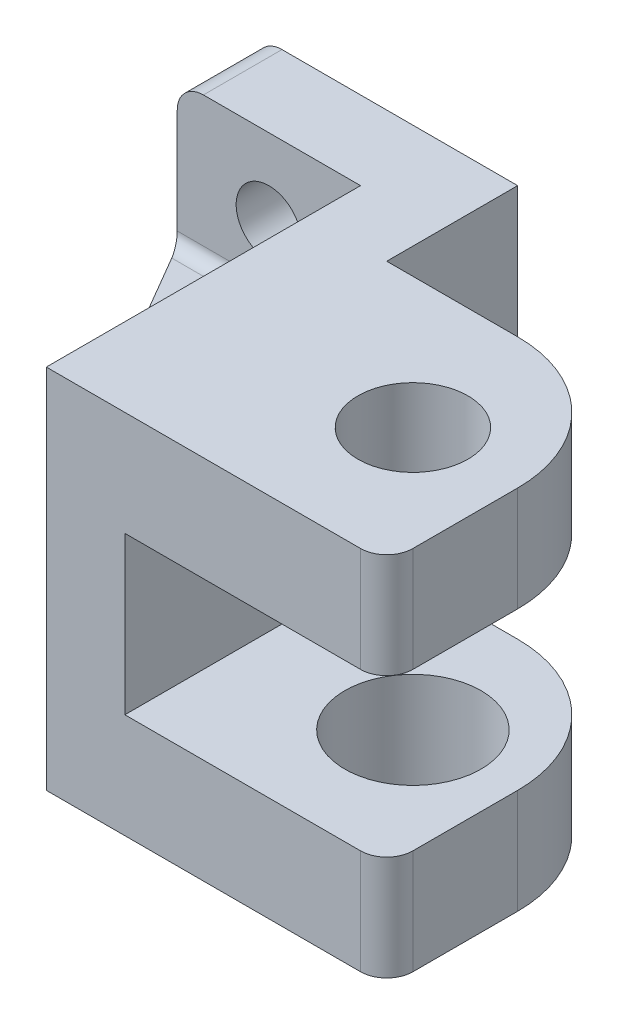
SolidWorks part; units mm, degrees
material "1023 碳钢板 (SS)"
ref_plane "前视基准面" through (0, 0, 0) normal (0, 0, 1) x (1, 0, 0)
ref_plane "上视基准面" through (0, 0, 0) normal (0, 1, 0) x (1, 0, 0)
ref_plane "右视基准面" through (0, 0, 0) normal (1, 0, 0) x (0, 0, -1)
sketch "草图1" plane through (0, 0, 0) normal (0, 0, 1) x (1, 0, 0)
  line L0 (0, 93.0117) -> (0, -75.7623) construction
  line L1 (-85.2651, 0) -> (88.5823, 0) construction
  line L3 (-5, 7) -> (5, 7)
  line L4 (-5, 7) -> (-5, -7)
  line L5 (-5, -7) -> (5, -7)
  line L6 (5, 7) -> (5, -7)
  line L7 (-5, 7) -> (5, -7) construction
  line L8 (-5, -7) -> (5, 7) construction
  point P5 (0, 0)
  dimension "D1" = 10
  dimension "D2" = 14
extrude "凸台-拉伸1" add sketch "草图1" along normal blind 3
sketch "草图2" plane through (0, 0, 3) normal (0, 0, 1) x (1, 0, 0)
  line L0 (-5, -7) -> (5, -7) construction
  line L1 (5, 7) -> (2, 7)
  line L2 (5, 7) -> (5, -7)
  line L3 (5, -7) -> (2, -7)
  line L4 (2, 7) -> (2, -7)
  dimension "D1" = 3
extrude "凸台-拉伸2" add sketch "草图2" along normal blind 12
ref_plane "基准面1" through (0, 0, 0) normal (0, -1, 0) x (-1, 0, 0)
sketch "草图3" plane through (0, 0, 0) normal (0, -1, 0) x (-1, 0, 0)
  line L0 (5, -3) -> (-2, -15)
rib "筋1" sketch "草图3" sketch "草图3" thickness 3 extrusion direction parallel to sketch draft on no parameters "D1"=3
sketch "草图4" plane through (0, 0, 3) normal (0, 0, 1) x (1, 0, 0)
  line L0 (-1.5, 8.5017) -> (-1.5, -9.8444) construction
  line L1 (-5, 7) -> (-5, 1.5) construction
  line L2 (-7.396, 0) -> (8.4395, 0) construction
  circle A0 centre (-1.5, 4) radius 1.5
  circle A1 centre (-1.5, -4) radius 1.5
  dimension "D2" = 8
  dimension "D3" = 3
  dimension "D1" = 3.5
hole_wizard "M3 螺纹孔2" positions "3D草图2" profile "草图6" tap size "M3" standard "GB" end condition up to next
sketch3d "3D草图2"
  point P0 (-1.5, 4, 3)
  point P3 (-1.5, -4, 3)
cosmetic thread "孔螺蚊线1" parameters "D2"=3
cosmetic thread "孔螺蚊线2" parameters "D2"=3
sketch "草图6" plane through (-1.5, 4, 3) normal (1, 0, 0) x (0, -1, 0)
  line L0 (0, 0) -> (0, 3)
  line L1 (0, 3) -> (1.25, 3)
  line L2 (1.25, 3) -> (1.25, 0)
  line L5 (1.25, 0) -> (0, 0)
  line L11 (0, -6.35) -> (0, 107.95) construction
  dimension "通孔螺纹孔钻头直径" = 2.5
  dimension "通孔螺纹孔钻头深度" = 3
sketch "草图7" plane through (5, 0, 0) normal (1, 0, 0) x (0, 0, -1)
  line L0 (-15, -7) -> (0, -7) construction
  line L1 (-15, -7) -> (-5, -7)
  line L2 (-15, -7) -> (-15, -3)
  line L3 (-15, -3) -> (-5, -3)
  line L4 (-5, -7) -> (-5, -3)
  line L5 (-16.4597, 0) -> (6.1543, 0) construction
  line L6 (-15, -7) -> (-15, 7) construction
  line L7 (-5, 7) -> (-5, 3)
  line L8 (-15, 3) -> (-5, 3)
  line L9 (-15, 7) -> (-15, 3)
  line L10 (-15, 7) -> (-5, 7)
  dimension "D1" = 4
  dimension "D2" = 10
extrude "凸台-拉伸3" add sketch "草图7" along normal blind 10
sketch "草图8" plane through (0, -7, 0) normal (0, -1, 0) x (1, 0, 0)
  line L0 (2, 15) -> (15, 15) construction
  line L1 (15, 15) -> (15, 5) construction
  circle A0 centre (11, 10) radius 2.6
  dimension "D1" = 5.2
  dimension "D2" = 5
  dimension "D3" = 4
fillet "圆角1" radius 1 2 edges at (15, 5, 15) (15, -5, 15)
fillet "圆角2" radius 0.5 4 edges at (2, 1.5, 9) (-1.5, 1.5, 3) (-1.5, -1.5, 3) (2, -1.5, 9)
fillet "圆角3" radius 1 2 edges at (-5, -7, 1.5) (-5, 7, 1.5)
extrude "切除-拉伸3" cut sketch "草图8" against normal blind 4
sketch "草图12" plane through (0, 7, 0) normal (0, 1, 0) x (1, 0, 0)
  line L0 (14, -15) -> (2, -15) construction
  line L1 (15, -5) -> (15, -14) construction
  point P0 (11, -10)
  dimension "D1" = 5
  dimension "D2" = 4
hole_wizard "M5 螺纹孔1" positions "草图13" profile "草图14" tap size "M5" standard "GB" end condition up to next
sketch "草图13" plane through (0, 7, 0) normal (0, 1, 0) x (1, 0, 0)
  point P0 (11, -10)
sketch "草图14" plane through (11, 7, 10) normal (1, 0, 0) x (0, 0, 1)
  line L0 (0, 0) -> (0, 4)
  line L1 (0, 4) -> (2.1, 4)
  line L2 (2.1, 4) -> (2.1, 0)
  line L5 (2.1, 0) -> (0, 0)
  line L11 (0, -6.35) -> (0, 107.95) construction
  dimension "通孔螺纹孔钻头直径" = 4.2
  dimension "通孔螺纹孔钻头深度" = 4
cosmetic thread "孔螺蚊线3" parameters "D2"=5
fillet "圆角5" radius 5 2 edges at (15, 5, 5) (15, -5, 5)
